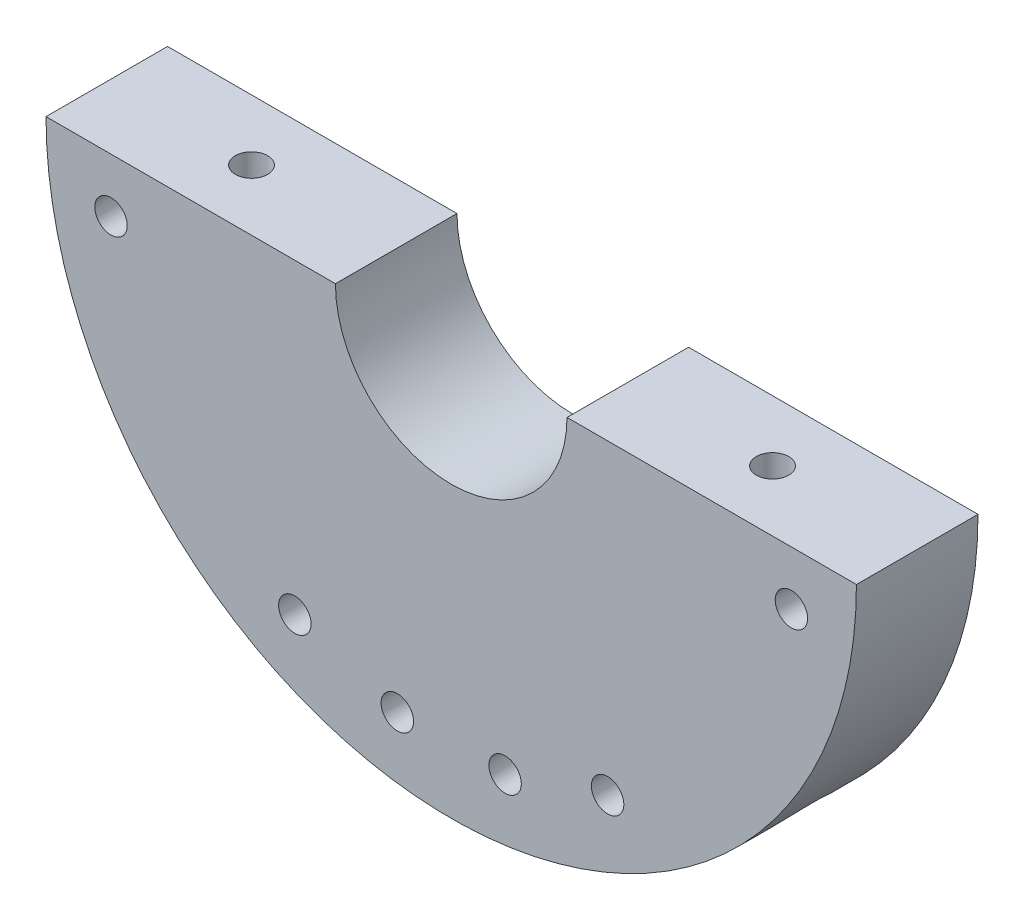
SolidWorks part; units mm, degrees
ref_plane "Płaszczyzna przednia" through (0, 0, 0) normal (0, 0, 1) x (1, 0, 0)
ref_plane "Płaszczyzna górna" through (0, 0, 0) normal (0, 1, 0) x (1, 0, 0)
ref_plane "Płaszczyzna prawa" through (0, 0, 0) normal (1, 0, 0) x (0, 0, -1)
sketch "Szkic1" plane through (0, 0, 0) normal (0, 0, 1) x (1, 0, 0)
  line L0 (-100, 0) -> (-28.575, 0)
  line L1 (28.575, 0) -> (100, 0)
  arc A0 (-28.575, 0) -> (28.575, 0) centre (0, 0) ccw
  arc A1 (-100, 0) -> (100, 0) centre (0, 0) ccw
  dimension "D1" = 57.15
  dimension "D2" = 200
extrude "Dodanie-wyciągnięcie1" add sketch "Szkic1" along normal blind 30
sketch "Szkic2" plane through (0, 0, 0) normal (0, 1, 0) x (1, 0, 0)
  circle A0 centre (-64.2875, -15) radius 4
  circle A1 centre (64.2875, -15) radius 4
  dimension "D1" = 8
  dimension "D2" = 8
extrude "Wytnij-wyciągnięcie1" cut sketch "Szkic2" against normal through all
ref_plane "Płaszczyzna1" through (0, -15, 0) normal (0, 1, 0) x (1, 0, 0)
sketch "Szkic3" plane through (0, -15, 0) normal (0, 1, 0) x (1, 0, 0)
  circle A0 centre (64.2875, -15) radius 10
  circle A1 centre (-64.2875, -15) radius 10
  dimension "D1" = 20
  dimension "D2" = 20
extrude "Wytnij-wyciągnięcie2" cut sketch "Szkic3" against normal through all
sketch "Szkic5" plane through (0, 0, 0) normal (0, 0, -1) x (-1, 0, 0)
  line L0 (0, 0) -> (0, -85)
  line L1 (0, -85) -> (0, 0)
  line L2 (0, 0) -> (-38.5892, -75.7356)
  circle A1 centre (-38.5892, -75.7356) radius 4
  circle A7 centre (-83.9535, -13.2969) radius 4
  circle A29 centre (83.9535, -13.2969) radius 4
  circle A35 centre (38.5892, -75.7356) radius 4
  circle A37 centre (13.2969, -83.9535) radius 4
  circle A39 centre (-13.2969, -83.9535) radius 4
  arc A40 (-84.4861, -9.3325) -> (84.4861, -9.3325) centre (0, 0) ccw
  arc A41 (-84.4861, -9.3325) -> (84.4861, -9.3325) centre (0, 0) ccw
  arc A42 (-84.4861, -9.3325) -> (84.4861, -9.3325) centre (0, 0) ccw
  arc A43 (-84.4861, -9.3325) -> (84.9871, -1.4835) centre (0, 0) ccw
  arc A44 (-84.4861, -9.3325) -> (84.9871, -1.4835) centre (0, 0) ccw
  arc A45 (-84.4861, -9.3325) -> (84.9871, -1.4835) centre (0, 0) ccw
  arc A46 (-84.4861, -9.3325) -> (84.9871, -1.4835) centre (0, 0) ccw
  arc A47 (-84.4861, -9.3325) -> (84.9871, -1.4835) centre (0, 0) ccw
  arc A48 (-84.4861, -9.3325) -> (84.9871, -1.4835) centre (0, 0) ccw
  arc A49 (-84.4861, -9.3325) -> (84.9871, -1.4835) centre (0, 0) ccw
  arc A50 (-84.4861, -9.3325) -> (84.9871, -1.4835) centre (0, 0) ccw
  arc A51 (-84.4861, -9.3325) -> (84.9871, -1.4835) centre (0, 0) ccw
  arc A52 (-84.4861, -9.3325) -> (84.9871, -1.4835) centre (0, 0) ccw
  arc A53 (-84.4861, -9.3325) -> (84.9871, -1.4835) centre (0, 0) ccw
  arc A54 (-84.4861, -9.3325) -> (84.9871, -1.4835) centre (0, 0) ccw
  arc A55 (-84.4861, -9.3325) -> (84.9871, -1.4835) centre (0, 0) ccw
  arc A56 (-84.4861, -9.3325) -> (84.9871, -1.4835) centre (0, 0) ccw
  arc A57 (-84.4861, -9.3325) -> (84.9871, -1.4835) centre (0, 0) ccw
  arc A58 (-84.4861, -9.3325) -> (84.9871, -1.4835) centre (0, 0) ccw
  arc A59 (-84.4861, -9.3325) -> (84.9871, -1.4835) centre (0, 0) ccw
  circle A64 centre (-83.9535, 13.2969) radius 4 [skipped]
  circle A66 centre (-75.7356, 38.5892) radius 4 [skipped]
  circle A68 centre (-60.1041, 60.1041) radius 4 [skipped]
  circle A70 centre (-38.5892, 75.7356) radius 4 [skipped]
  circle A72 centre (-13.2969, 83.9535) radius 4 [skipped]
  circle A74 centre (13.2969, 83.9535) radius 4 [skipped]
  circle A76 centre (38.5892, 75.7356) radius 4 [skipped]
  circle A78 centre (60.1041, 60.1041) radius 4 [skipped]
  circle A80 centre (75.7356, 38.5892) radius 4 [skipped]
  circle A82 centre (83.9535, 13.2969) radius 4 [skipped]
  arc A89 (62.8652, -57.2099) -> (57.2099, -62.8652) centre (60.1041, -60.1041) ccw [skipped]
  arc A90 (73.8362, -42.1095) -> (77.4672, -34.9834) centre (75.7356, -38.5892) ccw [skipped]
  arc A91 (-73.8362, -42.1095) -> (-77.4672, -34.9834) centre (-75.7356, -38.5892) ccw [skipped]
  arc A92 (-62.8652, -57.2099) -> (-57.2099, -62.8652) centre (-60.1041, -60.1041) ccw [skipped]
  point P65 (0, 0)
  dimension "D3" = 8
  dimension "D2" = 27
  dimension "D4" = 20
extrude "Wytnij-wyciągnięcie5" cut sketch "Szkic5" against normal through all contours A40 A29 | A29 A40 | A40 A35 | A35 A40 | A40 A37 | A37 A40 | A40 A39 | A39 A40 | A40 A1 | A1 A40 L2 | L2 A40 A1 | A40 A7 | A7 A40
